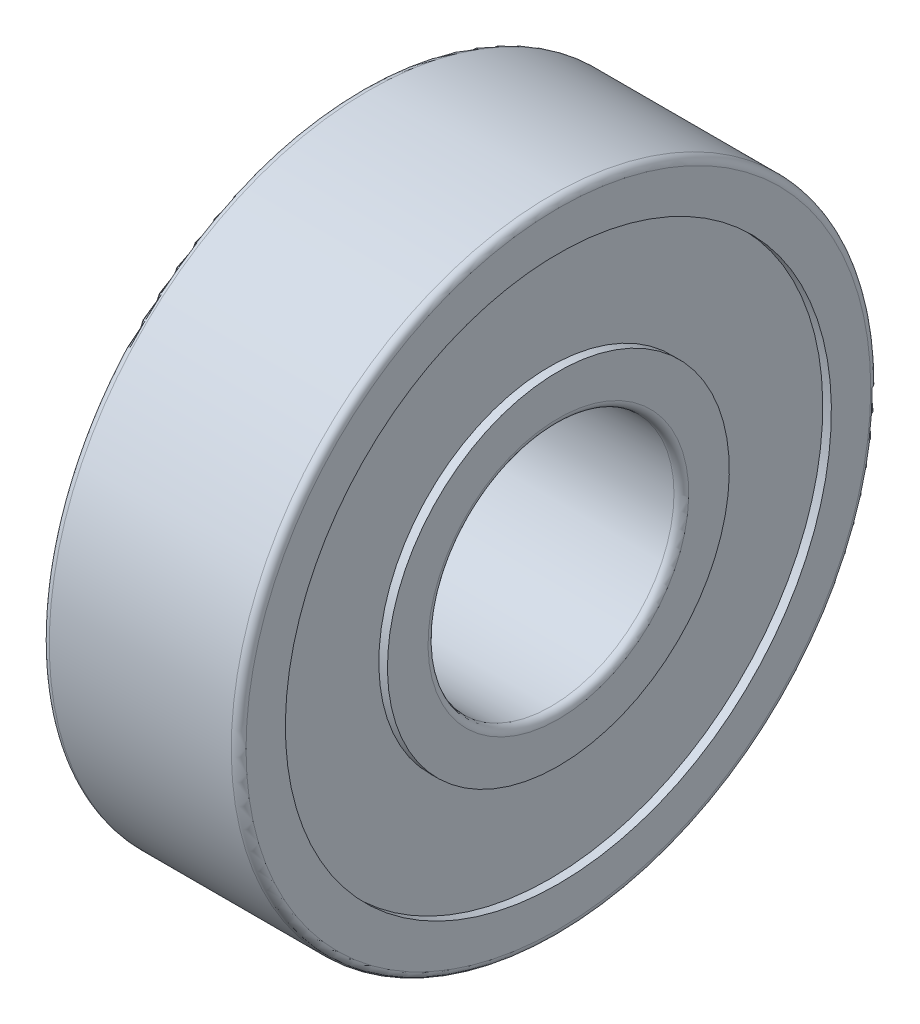
SolidWorks part; units mm, degrees
ref_plane "Front Plane" through (0, 0, 0) normal (0, 0, 1) x (1, 0, 0)
ref_plane "Top Plane" through (0, 0, 0) normal (0, 1, 0) x (1, 0, 0)
ref_plane "Right Plane" through (0, 0, 0) normal (1, 0, 0) x (0, 0, -1)
sketch "Sketch1" plane through (0, 0, 0) normal (0, 0, 1) x (1, 0, 0)
  line L0 (0, 0) -> (8, 0) construction
  line L1 (0, 5) -> (0, 6.95)
  line L2 (0, 6.95) -> (0.35, 6.95)
  line L3 (0.35, 6.95) -> (0.35, 11.1)
  line L4 (0.35, 11.1) -> (0, 11.1)
  line L5 (0, 11.1) -> (0, 13)
  line L6 (0, 13) -> (8, 13)
  line L7 (8, 13) -> (8, 11.1)
  line L8 (8, 11.1) -> (7.65, 11.1)
  line L9 (7.65, 11.1) -> (7.65, 6.95)
  line L10 (7.65, 6.95) -> (8, 6.95)
  line L11 (8, 6.95) -> (8, 5)
  line L12 (8, 5) -> (0, 5)
  dimension "D_s" = 10
  dimension "D" = 26
  dimension "B" = 8
  dimension "MSM_3" = 13.9
  dimension "MSM_4" = 22.2
  dimension "MSM_5" = 7.3
revolve "Revolve1" add sketch "Sketch1" angle 360 about L0
fillet "Fillet1" radius 0.3 4 edges at (0, -5, 0) (8, -5, 0) (0, -13, 0) (8, -13, 0)
